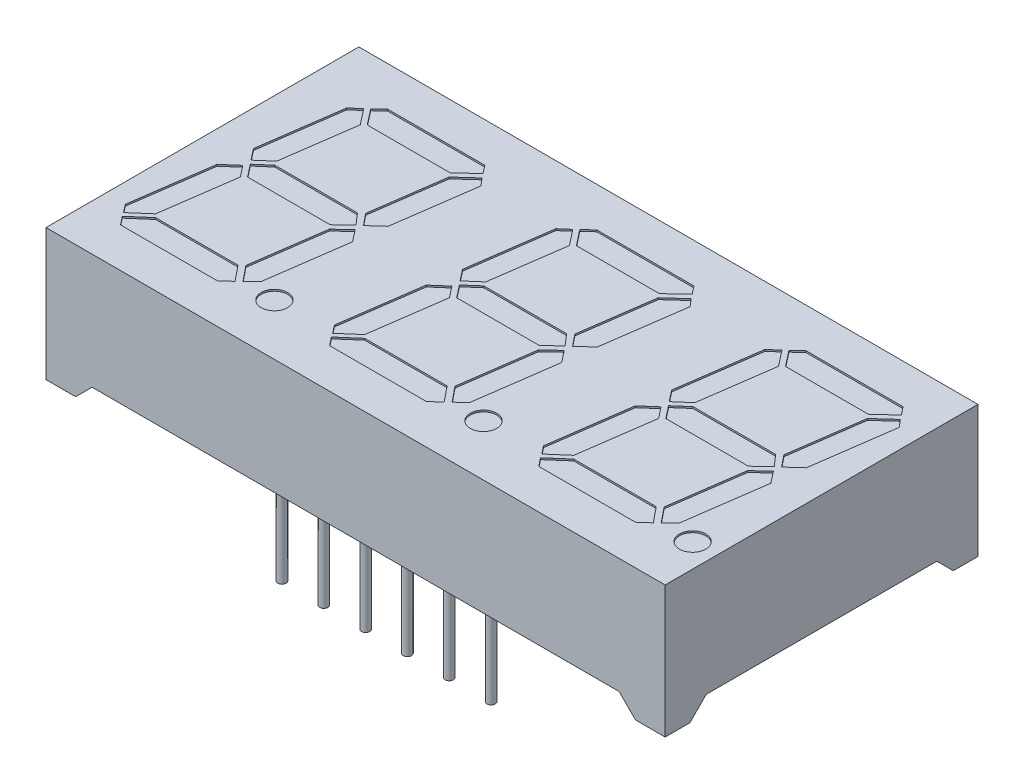
SolidWorks part; units mm, degrees
ref_plane "Front Plane" through (0, 0, 0) normal (0, 0, 1) x (1, 0, 0)
ref_plane "Top Plane" through (0, 0, 0) normal (0, 1, 0) x (1, 0, 0)
ref_plane "Right Plane" through (0, 0, 0) normal (1, 0, 0) x (0, 0, -1)
sketch "Sketch1" plane through (0, 0, 0) normal (0, 1, 0) x (1, 0, 0)
  line L1 (-18.8, 9.5) -> (18.8, 9.5)
  line L2 (-18.8, 9.5) -> (-18.8, -9.5)
  line L3 (-18.8, -9.5) -> (18.8, -9.5)
  line L4 (18.8, 9.5) -> (18.8, -9.5)
  line L5 (-18.8, 9.5) -> (18.8, -9.5) construction
  line L6 (-18.8, -9.5) -> (18.8, 9.5) construction
  point P0 (0, 0)
  dimension "D1" = 37.6
  dimension "D2" = 19
extrude "Boss-Extrude1" add sketch "Sketch1" against normal blind 8
sketch "Sketch2" plane through (0, 0, 0) normal (0, 1, 0) x (1, 0, 0)
  line L0 (-0.6958, 7.0997) -> (-0.6958, -7.1003) construction
  line L1 (-1.9522, 7.1) -> (3.9478, 7.1)
  line L2 (0, 0) -> (0, 7.1) construction
  line L3 (-3.9745, -7.1) -> (1.8962, -7.1)
  line L4 (0, 0) -> (0.9978, 7.1) construction
  line L5 (3.9478, 7.1) -> (4.3303, 6.6105) construction
  line L6 (-1.9522, 7.1) -> (-2.4598, 6.6266) construction
  line L7 (-1.7396, 5.65) -> (3.3003, 5.65)
  line L8 (-3.2953, -5.65) -> (1.7105, -5.65)
  line L9 (-2.4362, 0.725) -> (2.5889, 0.725)
  line L10 (-2.6343, -0.725) -> (2.3788, -0.725)
  line L11 (-3.2578, 5.9201) -> (-3.9559, 0.9527)
  line L12 (-1.9611, 5.4462) -> (-2.5872, 0.9912)
  line L13 (4.9183, 5.895) -> (4.2238, 0.9532)
  line L14 (3.4859, 5.4032) -> (2.8604, 0.9528)
  line L15 (-4.2274, -0.9791) -> (-4.9148, -5.87)
  line L16 (-2.8586, -0.9399) -> (-3.493, -5.4534)
  line L17 (3.9577, -0.94) -> (3.2727, -5.8142)
  line L18 (2.5889, -0.9793) -> (1.9639, -5.4264)
  line L19 (-1.7396, 5.65) -> (-2.4846, 6.6035)
  line L20 (3.9577, -0.94) -> (3.3985, -0.2243)
  line L21 (-3.394, -0.2546) -> (-2.8586, -0.9399)
  line L22 (-2.7061, 6.3997) -> (-1.9611, 5.4462)
  line L23 (-1.9522, 7.1) -> (-2.4846, 6.6035)
  line L24 (3.3003, 5.65) -> (4.3303, 6.6105)
  line L25 (3.9478, 7.1) -> (4.3303, 6.6105)
  line L26 (-3.2578, 5.9201) -> (-2.7061, 6.3997)
  line L27 (-3.9559, 0.9527) -> (-3.4202, 0.2671)
  line L28 (-3.4202, 0.2671) -> (-2.5872, 0.9912)
  line L29 (-4.2274, -0.9791) -> (-3.394, -0.2546)
  line L30 (-4.9148, -5.87) -> (-4.5335, -6.358)
  line L31 (-4.5335, -6.358) -> (-3.493, -5.4534)
  line L32 (-2.4362, 0.725) -> (-3.2288, 0.036)
  line L33 (-3.2288, 0.036) -> (-2.6343, -0.725)
  line L34 (2.5889, 0.725) -> (3.191, 0.0324)
  line L35 (3.191, 0.0324) -> (2.3788, -0.725)
  line L36 (2.5889, -0.9793) -> (3.3985, -0.2243)
  line L37 (-3.9745, -7.1) -> (-4.3779, -6.5911)
  line L38 (-4.3779, -6.5911) -> (-3.2953, -5.65)
  line L39 (1.7105, -5.65) -> (2.4723, -6.5911)
  line L40 (2.4723, -6.5911) -> (1.8962, -7.1)
  line L41 (1.9639, -5.4264) -> (2.718, -6.358)
  line L42 (2.718, -6.358) -> (3.2727, -5.8142)
  line L43 (2.8604, 0.9528) -> (3.4363, 0.2415)
  line L44 (3.4363, 0.2415) -> (4.2238, 0.9532)
  line L45 (3.4859, 5.4032) -> (4.5327, 6.3493)
  line L46 (4.5327, 6.3493) -> (4.9183, 5.895)
  circle A0 centre (4.65, -6.38) radius 0.8
  dimension "D48" = 1.6
  dimension "D1" = 14.2
  dimension "D2" = 7.1
  dimension "D3" = 14.2
  dimension "D4" = 5.9
  dimension "D5" = 1.45
  dimension "D6" = 1.45
  dimension "D7" = 0.725
  dimension "D8" = 1.45
  dimension "D9" = 4.05
  dimension "D10" = 1.35
  dimension "D11" = 8.1
  dimension "D12" = 1.35
  dimension "D13" = 4.05
  dimension "D14" = 1.35
  dimension "D15" = 8.1
  dimension "D16" = 1.35
  dimension "D17" = 46
  dimension "D18" = 0.3
  dimension "D19" = 95
  dimension "D20" = 137
  dimension "D21" = 128
  dimension "D22" = 137
  dimension "D23" = 95
  dimension "D24" = 128
  dimension "D25" = 1.21
  dimension "D26" = 1.21
  dimension "D27" = 87
  dimension "D28" = 134
  dimension "D29" = 139
  dimension "D30" = 0.3
  dimension "D31" = 87
  dimension "D32" = 139
  dimension "D33" = 134
  dimension "D34" = 87
  dimension "D37" = 139
  dimension "D38" = 87
  dimension "D39" = 134
  dimension "D40" = 93
  dimension "D41" = 139
  dimension "D42" = 128
  dimension "D43" = 92
  dimension "D44" = 131
  dimension "D45" = 137
  dimension "D46" = 6.38
  dimension "D47" = 4.65
extrude "Cut-Extrude2" cut sketch "Sketch2" against normal blind 0.1 contours L18 L41 L42 L17 L20 L36 | L40 L3 L37 L38 L8 L39 | A0 | L46 L13 L44 L43 L14 L45 | L25 L24 L7 L19 L23 L1 | L28 L12 L22 L26 L11 L27 | L35 L10 L33 L32 L9 L34 | L21 L16 L31 L30 L15 L29
pattern_linear "LPattern1" count 2 spacing 12.7 along (-1, 0, 0) count 2 spacing 12.7 along (1, 0, 0) of "Cut-Extrude2"
sketch "Sketch3" plane through (0, -8, 0) normal (0, -1, 0) x (1, 0, 0)
  line L14 (17.8, -8.5) -> (17.8, 8.5)
  line L15 (-17.8, -8.5) -> (17.8, -8.5)
  line L16 (-17.8, 8.5) -> (-17.8, -8.5)
  line L17 (17.8, 8.5) -> (-17.8, 8.5)
  line L18 (17.8, -8.5) -> (17.8, 8.5)
  line L19 (-17.8, -8.5) -> (17.8, -8.5)
  line L20 (-17.8, 8.5) -> (-17.8, -8.5)
  line L21 (17.8, 8.5) -> (-17.8, 8.5)
  dimension "D1" = 1
extrude "Cut-Extrude3" cut sketch "Sketch3" against normal blind 1
sketch "Sketch4" plane through (0, 0, -9.5) normal (0, 0, -1) x (-1, 0, 0)
  line L0 (-17, -8) -> (17, -8)
  line L1 (-18.8, -8) -> (18.8, -8) construction
  line L2 (-16, -7) -> (16, -7)
  line L3 (-17, -8) -> (-16, -7)
  line L4 (16, -7) -> (17, -8)
  point P5 (0, -8)
  point P8 (0, -7)
  dimension "D1" = 34
  dimension "D2" = 1
extrude "Cut-Extrude4" cut sketch "Sketch4" against normal up to surface (19 mm away) up to face at (0, -4, 9.5)
sketch "Sketch5" plane through (18.8, 0, 0) normal (1, 0, 0) x (0, 0, -1)
  line L0 (-8, -8) -> (8, -8)
  line L1 (-9.5, -8) -> (9.5, -8) construction
  line L2 (-7, -7) -> (7, -7)
  line L3 (-8, -8) -> (-7, -7)
  line L4 (7, -7) -> (8, -8)
  point P5 (0, -8)
  dimension "D1" = 16
  dimension "D2" = 1
extrude "Cut-Extrude5" cut sketch "Sketch5" against normal up to surface (37.6 mm away) up to face at (-18.8, -4, 0)
sketch "Sketch6" plane through (0, -7, 0) normal (0, -1, 0) x (1, 0, 0)
  line L0 (-6.35, -7.62) -> (-3.81, -7.62) construction
  circle A0 centre (-6.35, -7.62) radius 0.25
  circle A1 centre (-3.81, -7.62) radius 0.25
  circle A2 centre (-1.27, -7.62) radius 0.25
  circle A3 centre (1.27, -7.62) radius 0.25
  circle A4 centre (3.81, -7.62) radius 0.25
  circle A5 centre (6.35, -7.62) radius 0.25
  circle A6 centre (-3.81, 7.62) radius 0.25
  circle A7 centre (-1.27, 7.62) radius 0.25
  circle A8 centre (1.27, 7.62) radius 0.25
  circle A9 centre (3.81, 7.62) radius 0.25
  circle A10 centre (6.35, 7.62) radius 0.25
  circle A11 centre (-6.35, 7.62) radius 0.25
  dimension "D1" = 0.5
  dimension "D2" = 7.62
  dimension "D3" = 6.35
  dimension "D6" = 2.54
  dimension "D4" = 6
  dimension "D5" = 2
extrude "Boss-Extrude2" add sketch "Sketch6" along normal blind 6.3
